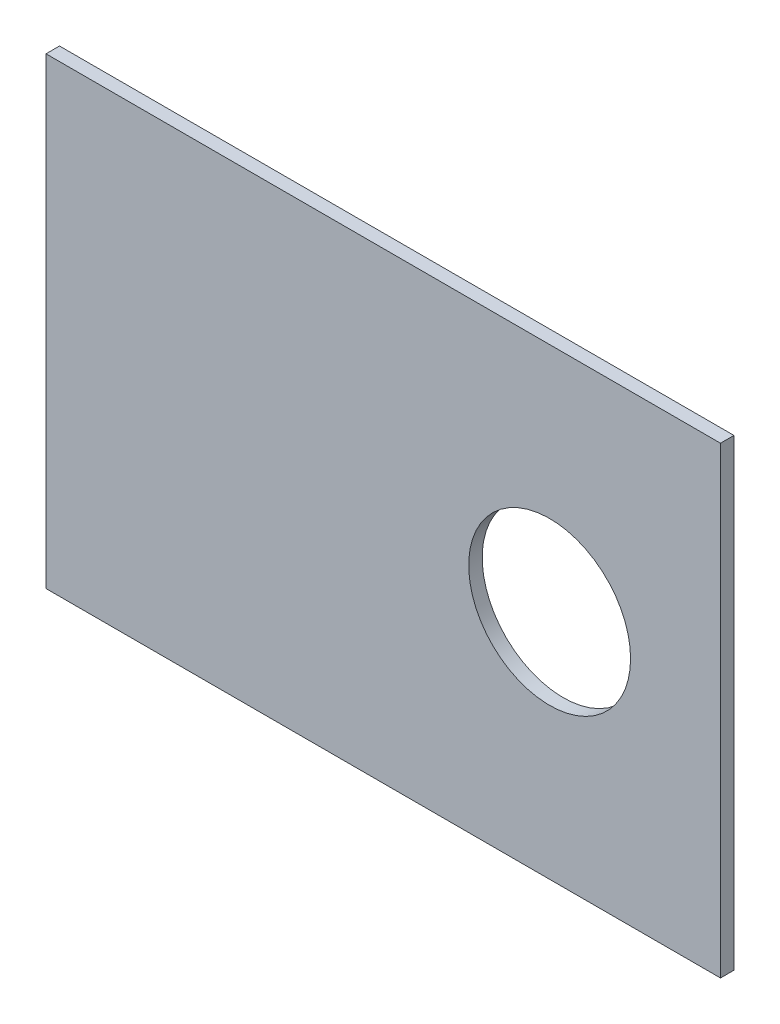
SolidWorks part; units mm, degrees
ref_plane "Alzado" through (0, 0, 0) normal (0, 0, 1) x (1, 0, 0)
ref_plane "Planta" through (0, 0, 0) normal (0, 1, 0) x (1, 0, 0)
ref_plane "Vista lateral" through (0, 0, 0) normal (1, 0, 0) x (0, 0, -1)
sketch "Croquis1" plane through (0, 0, 0) normal (0, 0, 1) x (1, 0, 0)
  line L0 (75, 0) -> (55, 0) construction
  line L1 (-75, -51.5) -> (75, -51.5)
  line L2 (-75, -51.5) -> (-75, 51.5)
  line L3 (-75, 51.5) -> (75, 51.5)
  line L4 (75, -51.5) -> (75, 51.5)
  line L5 (-75, -51.5) -> (75, 51.5) construction
  line L6 (-75, 51.5) -> (75, -51.5) construction
  line L7 (55, 0) -> (37, 0) construction
  circle A0 centre (37, 0) radius 18
  point P0 (0, 0)
  dimension "D1" = 150
  dimension "D2" = 103
  dimension "D3" = 20
  dimension "D4" = 18
extrude "Saliente-Extruir1" add sketch "Croquis1" along normal blind 3
